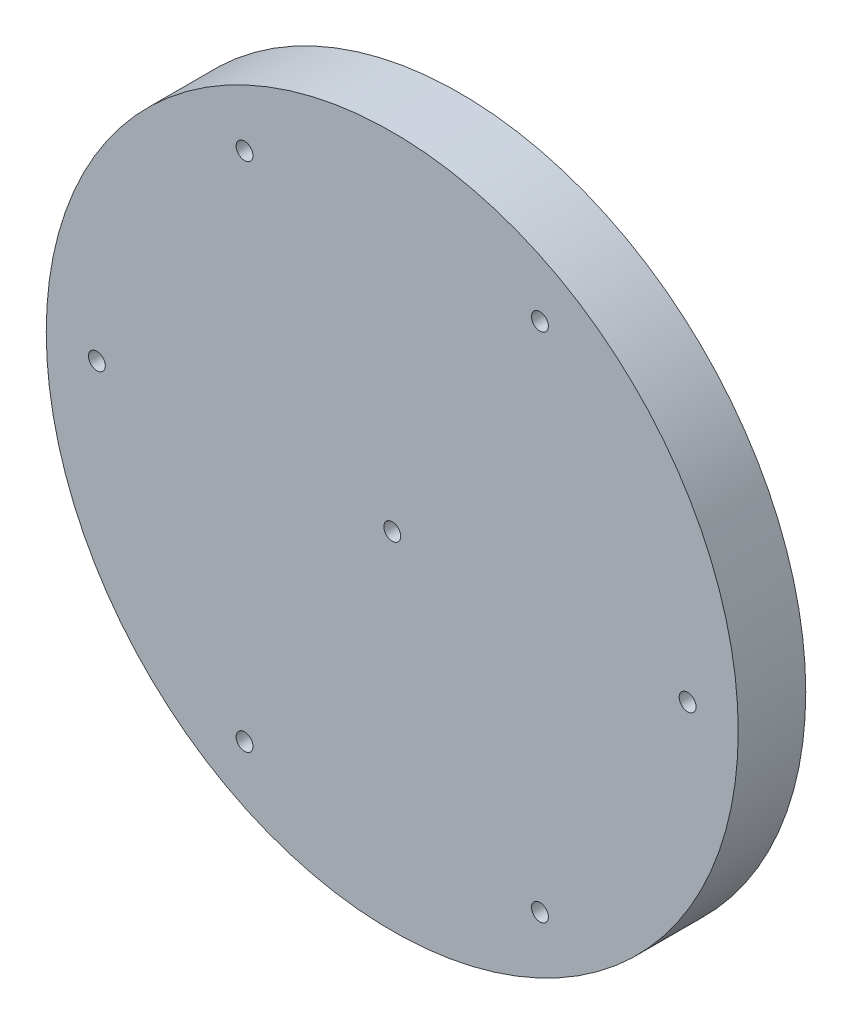
SolidWorks part; units mm, degrees
material "Acrylic (Medium-high impact)"
ref_plane "Front Plane" through (0, 0, 0) normal (0, 0, 1) x (1, 0, 0)
ref_plane "Top Plane" through (0, 0, 0) normal (0, 1, 0) x (1, 0, 0)
ref_plane "Right Plane" through (0, 0, 0) normal (1, 0, 0) x (0, 0, -1)
sketch "Model" plane through (0, 0, 0) normal (0, 0, 1) x (1, 0, 0)
  circle A224 centre (2103.9945, 1410.0632) radius 0.5
  circle A225 centre (2121.4945, 1410.0632) radius 0.5
  circle A226 centre (2112.7445, 1425.2187) radius 0.5
  circle A227 centre (2095.2445, 1425.2187) radius 0.5
  circle A228 centre (2086.4945, 1410.0632) radius 0.5
  circle A229 centre (2095.2445, 1394.9078) radius 0.5
  circle A230 centre (2112.7445, 1394.9078) radius 0.5
  circle A231 centre (2103.9945, 1410.0632) radius 20.5
extrude "Boss-Extrude1" add sketch "Model" along normal blind 4
